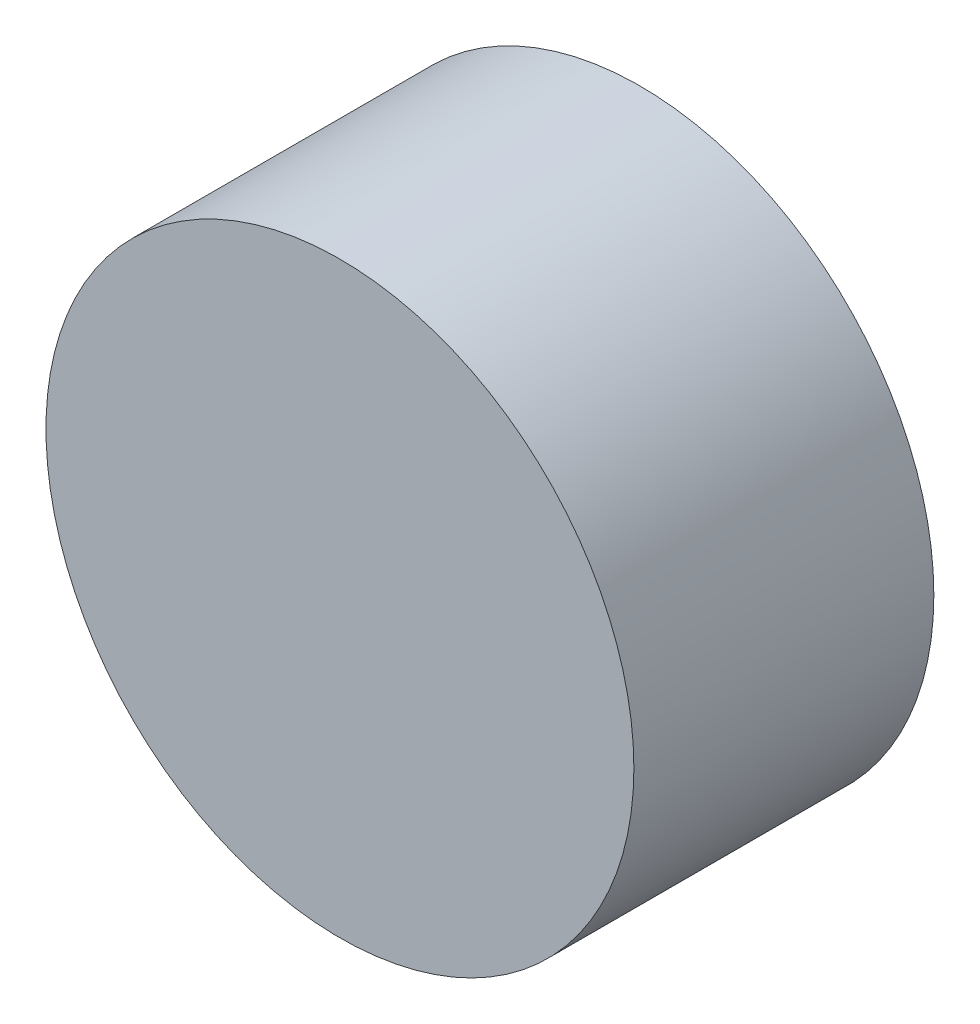
SolidWorks part; units mm, degrees
ref_plane "Alzado" through (0, 0, 0) normal (0, 0, 1) x (1, 0, 0)
ref_plane "Planta" through (0, 0, 0) normal (0, 1, 0) x (1, 0, 0)
ref_plane "Vista lateral" through (0, 0, 0) normal (1, 0, 0) x (0, 0, -1)
sketch "Croquis1" plane through (0, 0, 0) normal (0, 0, 1) x (1, 0, 0)
  circle A0 centre (0, 0) radius 12.25
  circle A1 centre (0, 0) radius 11.5
  dimension "D1" = 23
  dimension "D2" = 24.5
extrude "Saliente-Extruir1" add sketch "Croquis1" along normal blind 11
sketch "Croquis2" plane through (0, 0, 11) normal (0, 0, 1) x (1, 0, 0)
  circle A0 centre (0, 0) radius 12.25
extrude "Saliente-Extruir2" add sketch "Croquis2" along normal blind 1.5
